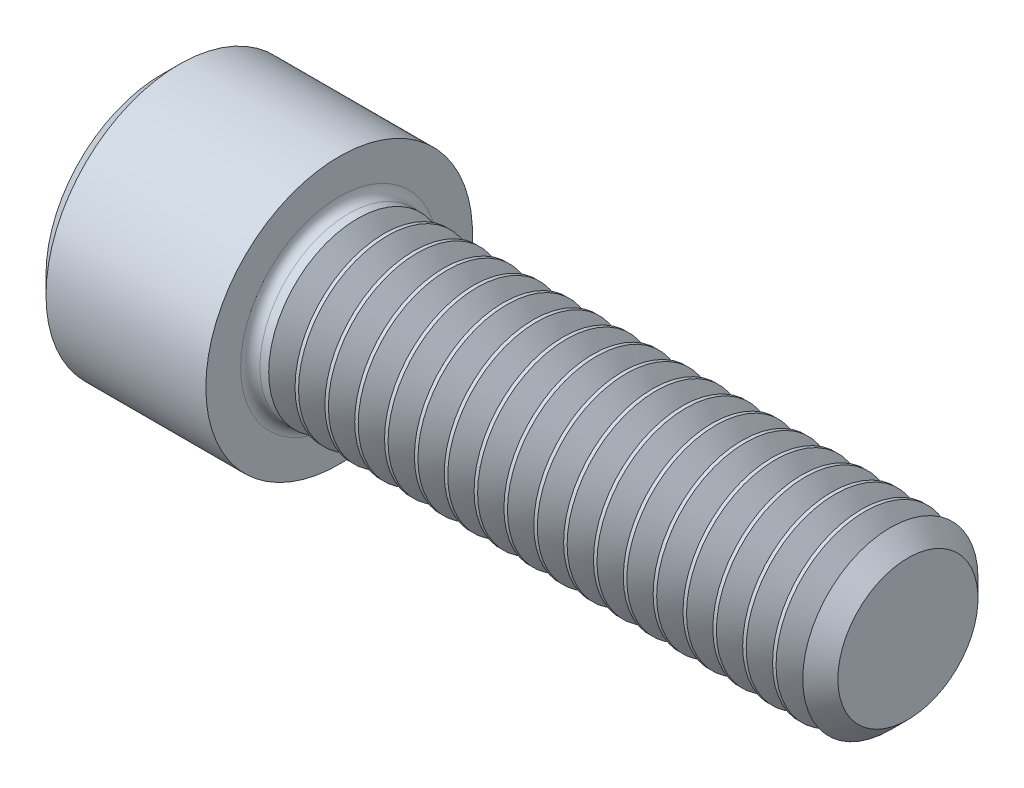
SolidWorks part; units mm, degrees
revolve "Base-Revolve" add sketch "BodySke"
sketch "BodySke" plane through (0, 0, 0) normal (0, 0, 1) x (1, 0, 0)
  line L0 (0, 0) -> (0, 5.1537)
  line L1 (0.8001, 5.9538) -> (7.9375, 5.9538)
  line L2 (7.9375, 5.9538) -> (7.9375, 3.9688)
  line L3 (7.9375, 3.9688) -> (32.498, 3.9688)
  line L4 (33.3375, 3.1293) -> (33.3375, 0)
  line L5 (33.3375, 0) -> (0, 0)
  line L6 (-31.75, 0) -> (127, 0) construction
  line L7 (0, 5.1537) -> (0.8001, 5.9538)
  line L8 (33.3375, 3.1293) -> (32.498, 3.9688)
  line L9 (0, -5.1537) -> (0.8001, -5.9538) construction
  line L10 (33.3375, -3.1293) -> (32.498, -3.9688) construction
  line L11 (9.3472, 9.525) -> (9.3472, 3.175) construction
  line L12 (7.9375, 9.525) -> (7.9375, 3.175) construction
  line L13 (-4.7625, 9.525) -> (-4.7625, 3.175) construction
  dimension "Diameter" = 7.9375
  dimension "Head_ht" = 7.9375
  dimension "Length" = 25.4
  dimension "Body_ch_ang" = 45
  dimension "Head_dia" = 11.9075
  dimension "Head_ch_ang" = 45
  dimension "Head_side_ht" = 7.1374
  dimension "Minor_dia" = 6.2586
  dimension "Advance" = 1.4097
  dimension "Thread_nom" = 25.4
  dimension "Thread_length" = 38.1
cosmetic thread "ThreadCosmetic" [suppressed]
fillet "Fillet1" radius 0.4318 1 edges at (7.9375, 0, 3.9688)
ref_plane "Plane1" through (0, 0, 0) normal (0, 0, 1) x (1, 0, 0)
ref_plane "Plane2" through (0, 0, 0) normal (0, 1, 0) x (1, 0, 0)
ref_plane "Plane3" through (0, 0, 0) normal (1, 0, 0) x (0, 0, -1)
other "Configuration Table"
sketch "Sketch2" plane through (0, 0, 0) normal (0, 0, 1) x (1, 0, 0)
  line L0 (0, 3.175) -> (3.8354, 3.175)
  line L1 (3.8354, 3.175) -> (5.6685, 0)
  line L2 (-31.75, 0) -> (127, 0) construction
  line L3 (5.6685, 0) -> (0, 0)
  line L4 (0, 0) -> (0, 3.175)
  line L5 (0, 5.1537) -> (0, -5.1537) construction
  line L6 (0, 0) -> (47.625, 0) construction
  line L7 (7.9375, -5.9538) -> (7.9375, 5.9538) construction
  dimension "D1" = 3.175
  dimension "D2" = 60
revolve "Hex-PreBroach" cut sketch "Sketch2" angle 360 about L6
sketch "Sketch3" plane through (0, 0, 0) normal (-1, 0, 0) x (0, 0.5, 0.866)
  line L0 (1.8331, 3.175) -> (-1.8331, 3.175)
  line L1 (-1.8331, 3.175) -> (-3.6662, 0)
  line L2 (1.8331, 3.175) -> (3.6662, 0)
  line L3 (1.8331, -3.175) -> (3.6662, 0)
  line L4 (1.8331, -3.175) -> (-1.8331, -3.175)
  line L5 (-1.8331, -3.175) -> (-3.6662, 0)
  dimension "D1" = 3.175
  dimension "D2" = 3.175
  dimension "Hex_size" = 6.35
extrude "Hex" cut sketch "Sketch3" against normal blind 3.8354
sketch "Sketch4" plane through (0, 0, 0) normal (-1, 0, 0) x (0, 0, 1)
  line L0 (0, 0) -> (3.7846, 0)
  line L1 (0, 0) -> (6.1484, 3.5498) construction
  line L2 (0, 0) -> (1.8923, 3.2776)
  line L3 (3.1235, 0.8061) -> (3.6229, 1.0945)
  line L4 (2.2599, 2.3019) -> (2.7593, 2.5903)
  arc A0 (3.1235, 0.8061) -> (2.2599, 2.3019) centre (0, 0) ccw
  arc A1 (3.7846, 0) -> (3.6229, 1.0945) centre (0, 0) ccw
  arc A2 (1.8923, 3.2776) -> (2.7593, 2.5903) centre (0, 0) cw
  dimension "D1" = 30
  dimension "D2" = 60
  dimension "Spline_p_dim" = 1.7272
  dimension "D3" = 0.8636
extrude "Spline" [suppressed] cut sketch "Sketch4" against normal blind 3.8354
pattern_circular "CirPattern1" [suppressed] count 6 every 60
sketch "Sketch5" plane through (0, 0, 0) normal (0, 0, 1) x (1, 0, 0)
  line L0 (-31.75, 0) -> (127, 0) construction
  line L2 (0, 5.1537) -> (0, -5.1537) construction
  circle A0 centre (2.6416, 0) radius 0.5905
  dimension "Drilled_hole_dia" = 1.1811
  dimension "Drilled_hole_loc" = 2.6416
extrude "Hole" [suppressed] cut sketch "Sketch5" against normal through all and the other way through all
pattern_circular "Drilled-4" [suppressed] count 2 every 60
pattern_circular "Drilled-6" [suppressed] count 3 every 60
sketch "ThdSchSke" plane through (0, 0, 0) normal (0, 0, 1) x (1, 0, 0)
  line L0 (9.3472, -3.1293) -> (8.7594, -3.9688)
  line L1 (9.3472, -3.1293) -> (9.935, -3.9688)
  line L2 (9.935, -3.9688) -> (9.935, -4.9609)
  line L3 (-3.175, 0) -> (5.1513, 0) construction
  line L5 (9.935, -4.9609) -> (8.7594, -4.9609)
  line L6 (8.7594, -4.9609) -> (8.7594, -3.9688)
  line L7 (0, 5.1537) -> (0, -5.1537) construction
  dimension "Thread_minor" = 6.2586
  dimension "Diameter" = 7.9375
  dimension "Start" = 9.3472
revolve "ThreadSchematic" cut sketch "ThdSchSke" angle 360 about L3
pattern_linear "ThdSchPat" count 18 spacing 1.3328 along (1, 0, 0) of "ThreadSchematic"
equation "\"D2@Sketch3\" = \"Hex_size@Sketch3\" / 2"
equation "\"D1@Sketch3\" = \"Hex_size@Sketch3\" / 2"
equation "\"D1@Sketch2\" = \"Hex_size@Sketch3\" / 2"
equation "\"D3@Sketch4\" = \"Spline_p_dim@Sketch4\" / 2"
equation "\"Thread_minor@ThreadCosmetic\"  =  \"Minor_dia@BodySke\""
equation "\"D2@CirPattern1\" = 360 / \"Num_teeth@CirPattern1\""
equation "\"Wall_thickness@Sketch2\" = \"Head_ht@BodySke\" - \"Key_eng@Hex\""
equation "\"Thread_length@ThreadCosmetic\" = ((sgn( (\"Length@BodySke\" - \"Advance@BodySke\" ) - \"Thread_nom@BodySke\" )-1)*( (\"Length@BodySke\" - \"Advance@BodySke\" ) - \"Thread_nom@BodySke\" ))/-2+ \"Thread_nom@BodySke\""
equation "\"Thread_minor@ThdSchSke\" = \"Minor_dia@BodySke\""
equation "\"Diameter@ThdSchSke\" = \"Diameter@BodySke\""
equation "\"Overcut@ThdSchSke\" = \"Diameter@BodySke\" * 1.25"
equation "\"Start@ThdSchSke\" = \"Head_ht@BodySke\" + \"Length@BodySke\" - \"Thread_length@ThreadCosmetic\"  '---Non-countersunk---"
equation "\"Num_threads@ThdSchPat\" = int( \"Thread_length@ThreadCosmetic\" / \"Advance@BodySke\" + 0.999 )  + 1"
equation "\"Advance@ThdSchPat\" = \"Thread_length@ThreadCosmetic\" /  (\"Num_threads@ThdSchPat\" - 1) 'relax it"
equation "\"Num_threads@ThdSchPat\" = \"Num_threads@ThdSchPat\" - sgn( \"Num_threads@ThdSchPat\" - 1) '---chamfered tips only---"
